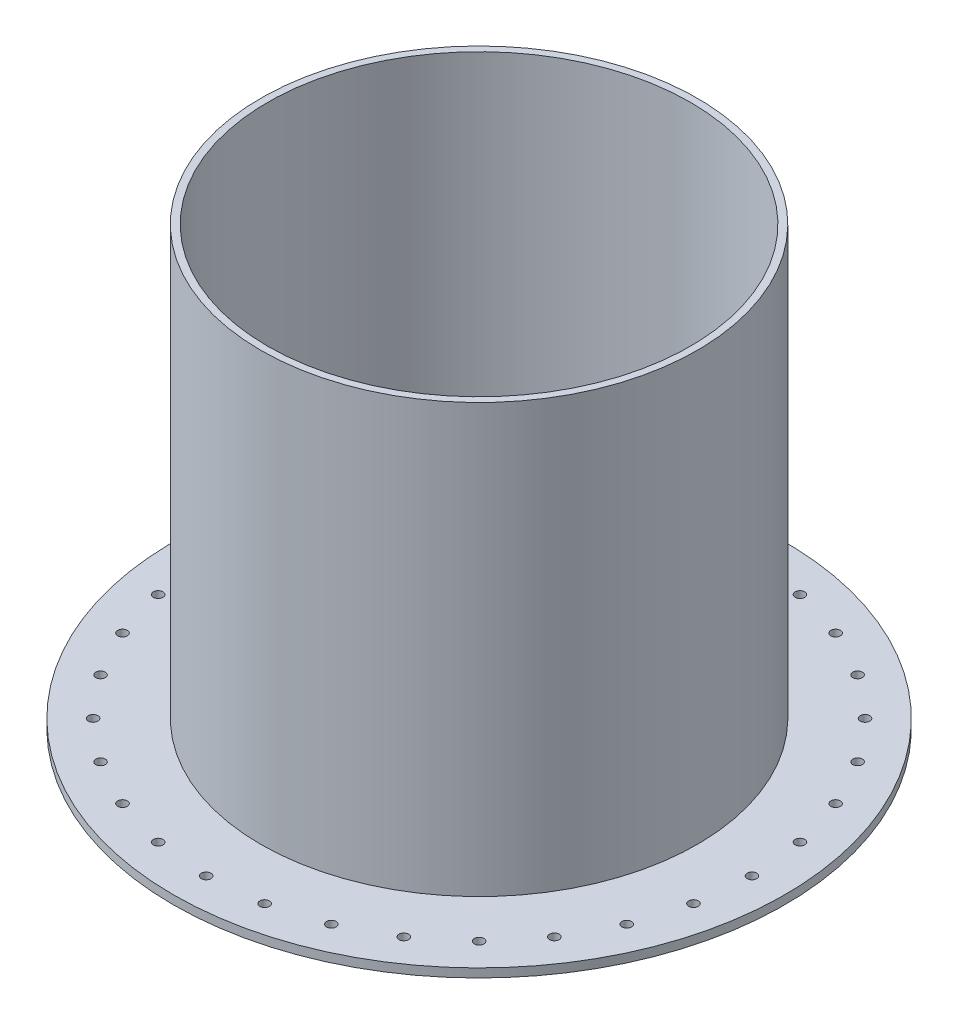
SolidWorks part; units mm, degrees
ref_plane "Front Plane" through (0, 0, 0) normal (0, 0, 1) x (1, 0, 0)
ref_plane "Top Plane" through (0, 0, 0) normal (0, 1, 0) x (1, 0, 0)
ref_plane "Right Plane" through (0, 0, 0) normal (1, 0, 0) x (0, 0, -1)
sketch "Sketch1" plane through (0, 0, 0) normal (0, 1, 0) x (1, 0, 0)
  circle A0 centre (0, 0) radius 500
  circle A1 centre (0, 0) radius 484
  dimension "D1" = 1000
  dimension "D2" = 968
extrude "Boss-Extrude1" add sketch "Sketch1" along normal blind 1000
sketch "Sketch2" plane through (0, 0, 0) normal (0, 1, 0) x (1, 0, 0)
  line L0 (0, 0) -> (0, 625) construction
  circle A0 centre (0, 0) radius 450
  circle A1 centre (0, 0) radius 700
  circle A2 centre (0, 625) radius 11
  circle A3 centre (121.9315, 612.9908) radius 11
  circle A4 centre (239.1771, 577.4247) radius 11
  circle A5 centre (347.2314, 519.6685) radius 11
  circle A6 centre (441.9417, 441.9417) radius 11
  circle A7 centre (519.6685, 347.2314) radius 11
  circle A8 centre (577.4247, 239.1771) radius 11
  circle A9 centre (612.9908, 121.9315) radius 11
  circle A10 centre (625, 0) radius 11
  circle A11 centre (612.9908, -121.9315) radius 11
  circle A12 centre (577.4247, -239.1771) radius 11
  circle A13 centre (519.6685, -347.2314) radius 11
  circle A14 centre (441.9417, -441.9417) radius 11
  circle A15 centre (347.2314, -519.6685) radius 11
  circle A16 centre (239.1771, -577.4247) radius 11
  circle A17 centre (121.9315, -612.9908) radius 11
  circle A18 centre (0, -625) radius 11
  circle A19 centre (-121.9315, -612.9908) radius 11
  circle A20 centre (-239.1771, -577.4247) radius 11
  circle A21 centre (-347.2314, -519.6685) radius 11
  circle A22 centre (-441.9417, -441.9417) radius 11
  circle A23 centre (-519.6685, -347.2314) radius 11
  circle A24 centre (-577.4247, -239.1771) radius 11
  circle A25 centre (-612.9908, -121.9315) radius 11
  circle A26 centre (-625, 0) radius 11
  circle A27 centre (-612.9908, 121.9315) radius 11
  circle A28 centre (-577.4247, 239.1771) radius 11
  circle A29 centre (-519.6685, 347.2314) radius 11
  circle A30 centre (-441.9417, 441.9417) radius 11
  circle A31 centre (-347.2314, 519.6685) radius 11
  circle A32 centre (-239.1771, 577.4247) radius 11
  circle A33 centre (-121.9315, 612.9908) radius 11
  point P71 (0, 0)
  dimension "D1" = 900
  dimension "D2" = 1400
  dimension "D4" = 22
  dimension "D3" = 625
  dimension "D5" = 32
extrude "Boss-Extrude2" add sketch "Sketch2" along normal blind 20
